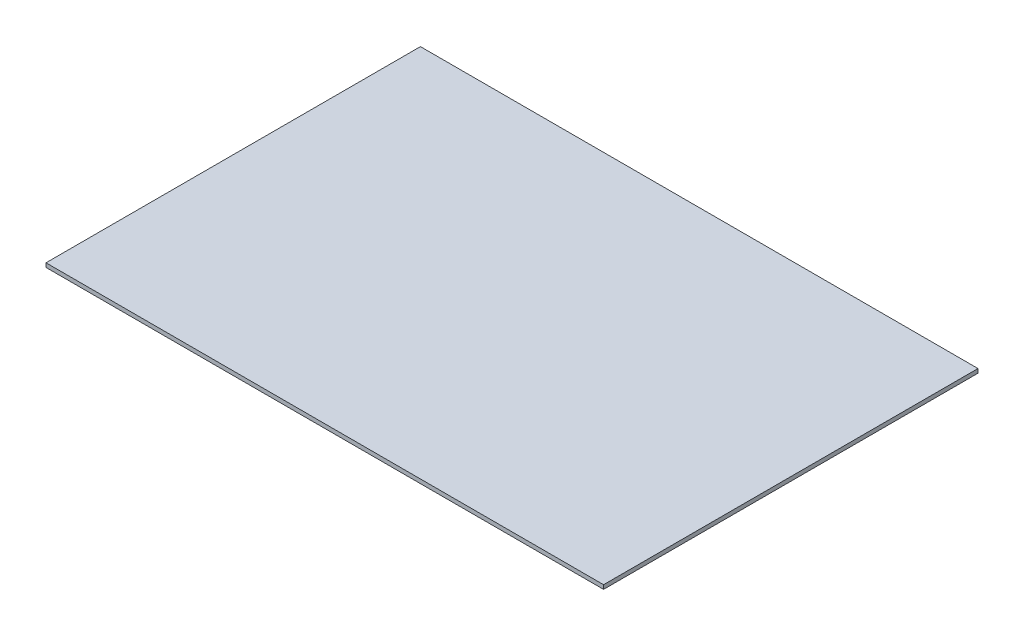
SolidWorks part; units mm, degrees
ref_plane "Front Plane" through (0, 0, 0) normal (0, 0, 1) x (1, 0, 0)
ref_plane "Top Plane" through (0, 0, 0) normal (0, 1, 0) x (1, 0, 0)
ref_plane "Right Plane" through (0, 0, 0) normal (1, 0, 0) x (0, 0, -1)
sketch "Sketch2" plane through (0, 0, 0) normal (0, 1, 0) x (1, 0, 0)
  line L1 (-137, 92) -> (137, 92)
  line L2 (-137, 92) -> (-137, -92)
  line L3 (-137, -92) -> (137, -92)
  line L4 (137, 92) -> (137, -92)
  line L5 (-137, 92) -> (137, -92) construction
  line L6 (-137, -92) -> (137, 92) construction
  point P0 (0, 0)
  dimension "D1" = 274
  dimension "D2" = 184
extrude "Boss-Extrude1" add sketch "Sketch2" along normal mid plane 2
